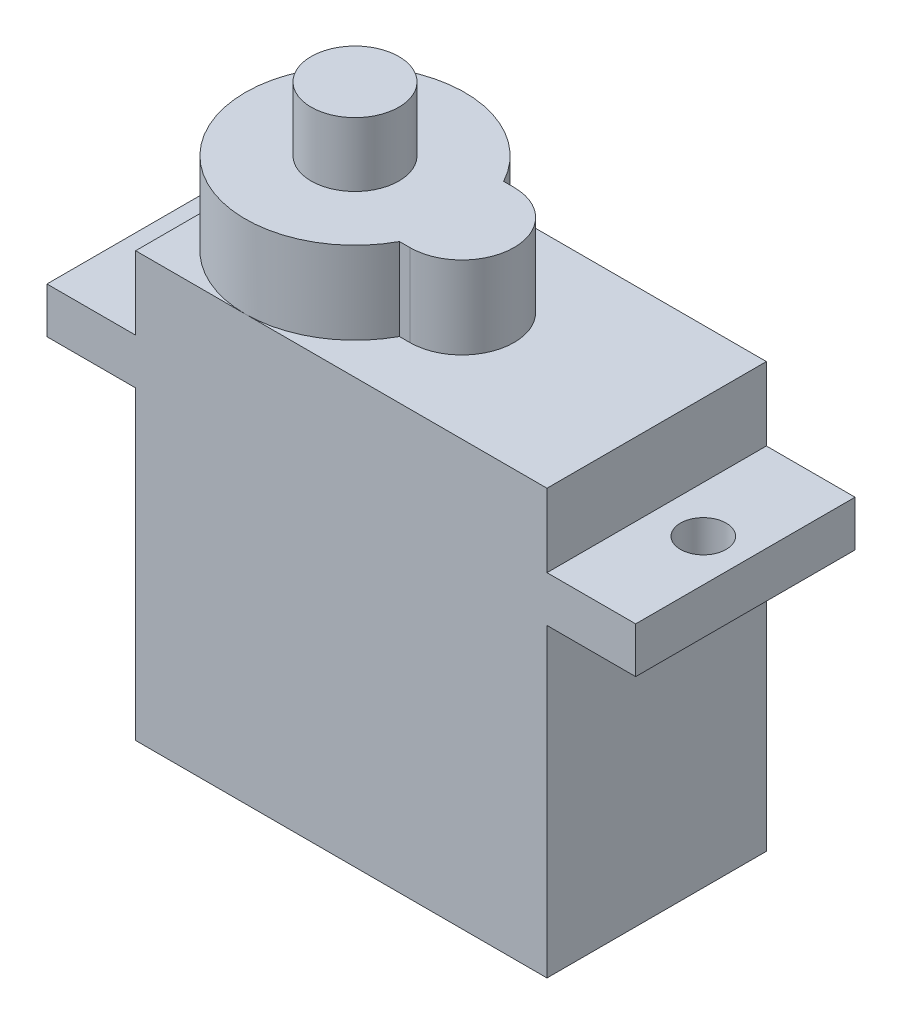
SolidWorks part; units mm, degrees
ref_plane "Спереди" through (0, 0, 0) normal (0, 0, 1) x (1, 0, 0)
ref_plane "Сверху" through (0, 0, 0) normal (0, 1, 0) x (1, 0, 0)
ref_plane "Справа" through (0, 0, 0) normal (1, 0, 0) x (0, 0, -1)
sketch "Sketch1" plane through (0, 0, 0) normal (0, 1, 0) x (1, 0, 0)
  line L0 (0, 0) -> (-44.4616, 0) construction
  line L1 (0, 0) -> (0, 54.7475) construction
  circle A0 centre (0, 0) radius 2.4
  dimension "D1" = 4.8
extrude "Вал" add sketch "Sketch1" along normal blind 3.5
sketch "Sketch2" plane through (0, 0, 0) normal (0, 1, 0) x (1, 0, 0)
  line L0 (0, 0) -> (11.5121, 0) construction
  line L1 (0, 0) -> (0, -6.8975) construction
  line L2 (8.7, -5.5297) -> (8.7, 7.465) construction
  line L3 (-6, -8.515) -> (-6, 9.0454) construction
  line L4 (5.85, -2.85) -> (5.2799, -2.85)
  line L5 (5.85, 2.85) -> (5.2799, 2.85)
  arc A2 (5.85, -2.85) -> (5.85, 2.85) centre (5.85, 0) ccw
  arc A3 (5.2799, 2.85) -> (5.2799, -2.85) centre (0, 0) ccw
  dimension "D3" = 14.7
extrude "Редуктор" add sketch "Sketch2" against normal blind 4.5
sketch "Sketch3" plane through (0, -4.5, 0) normal (0, -1, 0) x (-1, 0, 0)
  line L0 (0, 0) -> (-27.018, 0) construction
  line L1 (0, 0) -> (0, 13.6332) construction
  line L3 (-16.5, -6) -> (6, -6)
  line L4 (-16.5, -6) -> (-16.5, 6)
  line L5 (-16.5, 6) -> (6, 6)
  line L6 (6, -6) -> (6, 6)
  line L7 (-16.5, -6) -> (6, 6) construction
  line L8 (-16.5, 6) -> (6, -6) construction
  arc A2 (-5.2799, -2.85) -> (-5.2799, 2.85) centre (0, 0) ccw construction
  point P3 (-5.25, 0)
  dimension "D1" = 22.5
  dimension "D2" = 12
extrude "Корпус" add sketch "Sketch3" along normal blind 23.2
ref_plane "Plane1" through (0, -8.5, 0) normal (0, 1, 0) x (1, 0, 0)
sketch "Sketch4" plane through (0, -8.5, 0) normal (0, 1, 0) x (1, 0, 0)
  line L0 (-9.3905, 0) -> (21.2577, 0) construction
  line L1 (5.25, 12.903) -> (5.25, -13.0739) construction
  line L2 (-6, 0) -> (-6, 6) construction
  line L3 (-10.85, -6) -> (21.35, -6)
  line L4 (-10.85, -6) -> (-10.85, 6)
  line L5 (-10.85, 6) -> (21.35, 6)
  line L6 (21.35, -6) -> (21.35, 6)
  line L7 (-10.85, -6) -> (21.35, 6) construction
  line L8 (-10.85, 6) -> (21.35, -6) construction
  line L9 (16.5, 6) -> (16.5, -6) construction
  point P5 (5.25, 0)
  dimension "D1" = 32.2
extrude "Фланец" add sketch "Sketch4" against normal blind 2.5
sketch "Sketch5" plane through (0, 0, 0) normal (0, 1, 0) x (1, 0, 0)
  line L0 (-13.4183, 0) -> (23.0026, 0) construction
  line L1 (-8.55, 2.2792) -> (-8.55, -2.3808) construction
  line L4 (19.05, 2.2792) -> (19.05, -2.3808) construction
  line L7 (-10.85, 6) -> (-10.85, -6) construction
  line L8 (21.35, -6) -> (21.35, 6) construction
  circle A0 centre (-8.55, 0) radius 1.25
  circle A1 centre (19.05, 0) radius 1.25
  dimension "D1" = 2.5
  dimension "D2" = 2.3
  dimension "D3" = 2.3
extrude "Cut-Extrude1" cut sketch "Sketch5" against normal through all
